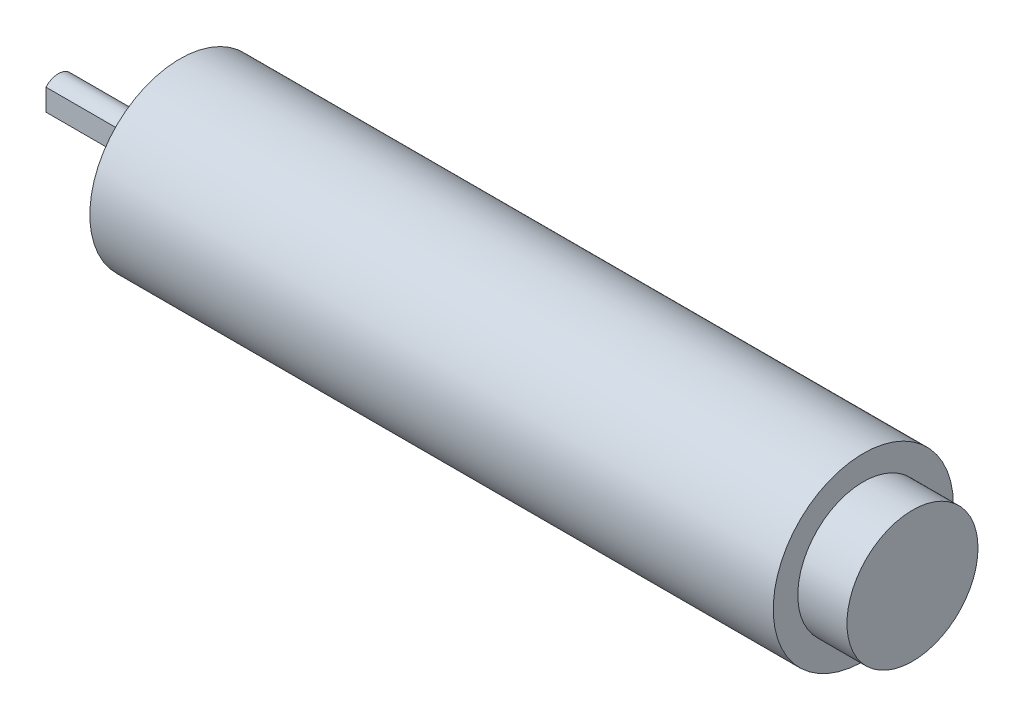
SolidWorks part; units mm, degrees
ref_plane "Front Plane" through (0, 0, 0) normal (0, 0, 1) x (1, 0, 0)
ref_plane "Top Plane" through (0, 0, 0) normal (0, 1, 0) x (1, 0, 0)
ref_plane "Right Plane" through (0, 0, 0) normal (1, 0, 0) x (0, 0, -1)
sketch "Sketch1" plane through (0, 0, 0) normal (0, 0, 1) x (1, 0, 0)
  line L0 (0, 11) -> (0, 0)
  line L1 (0, 0) -> (52.6, 0)
  line L2 (52.6, 0) -> (52.6, 11)
  line L3 (52.6, 11) -> (0, 11)
  line L4 (0, 0) -> (52.6, 0) construction
revolve "Revolve1" add sketch "Sketch1" angle 360 about L4
sketch "Sketch2" plane through (0, 0, 0) normal (-1, 0, 0) x (0, 0, 1)
  circle A0 centre (0, 0) radius 5
extrude "Boss-Extrude1" add sketch "Sketch2" along normal blind 1.35
sketch "Sketch3" plane through (-1.35, 0, 0) normal (-1, 0, 0) x (0, 0, 1)
  circle A0 centre (0, 0) radius 3.5
extrude "Boss-Extrude2" add sketch "Sketch3" along normal blind 1.8
sketch "Sketch4" plane through (-3.15, 0, 0) normal (-1, 0, 0) x (0, 0, 1)
  circle A0 centre (0, 0) radius 2
extrude "Boss-Extrude3" add sketch "Sketch4" along normal blind 11.7
ref_plane "Plane1" through (-3.675, 0, 3.675) normal (0.7071, 0, -0.7071) x (0, 1, 0)
sketch "Sketch6" plane through (-14.85, 0, 0) normal (-1, 0, 0) x (0, 0, 1)
  line L0 (1.5, 1.3229) -> (1.5, -1.3229)
  arc A0 (1.5, -1.3229) -> (1.5, 1.3229) centre (0, 0) ccw
extrude "Cut-Extrude1" cut sketch "Sketch6" against normal up to surface up to plane "Plane1"
hole_wizard "Hole1" positions "Sketch8" profile "Sketch7" legacy
sketch "Sketch8" plane through (0, 0, 0) normal (-1, 0, 0) x (0, 0, 1)
  point P0 (7, 0)
sketch "Sketch7" plane through (0, 0, 7) normal (0, 1, 0) x (0, 0, 1)
  line L0 (0, 0) -> (0, 6.5)
  line L1 (0, 6.5) -> (0.975, 6.5)
  line L2 (0.975, 6.5) -> (0.975, 0)
  line L3 (0.975, 0) -> (0, 0)
  line L4 (0, 110) -> (0, -10) construction
  dimension "Diameter" = 1.95
  dimension "Depth" = 6.5
hole_wizard "Hole2" positions "Sketch10" profile "Sketch9" legacy
sketch "Sketch10" plane through (0, 0, 0) normal (-1, 0, 0) x (0, 0, 1)
  point P0 (-3.5, -6.0622)
sketch "Sketch9" plane through (0, -6.0622, -3.5) normal (0, 1, 0) x (0, 0, 1)
  line L0 (0, 0) -> (0, 6.5)
  line L1 (0, 6.5) -> (0.975, 6.5)
  line L2 (0.975, 6.5) -> (0.975, 0)
  line L3 (0.975, 0) -> (0, 0)
  line L4 (0, 110) -> (0, -10) construction
  dimension "Diameter" = 1.95
  dimension "Depth" = 6.5
hole_wizard "Hole3" positions "Sketch12" profile "Sketch11" legacy
sketch "Sketch12" plane through (0, 0, 0) normal (-1, 0, 0) x (0, 0, 1)
  point P0 (-3.5, 6.0622)
sketch "Sketch11" plane through (0, 6.0622, -3.5) normal (0, 1, 0) x (0, 0, 1)
  line L0 (0, 0) -> (0, 6.5)
  line L1 (0, 6.5) -> (0.975, 6.5)
  line L2 (0.975, 6.5) -> (0.975, 0)
  line L3 (0.975, 0) -> (0, 0)
  line L4 (0, 110) -> (0, -10) construction
  dimension "Diameter" = 1.95
  dimension "Depth" = 6.5
hole_wizard "Hole4" positions "Sketch14" profile "Sketch13" legacy
sketch "Sketch14" plane through (52.6, 0, 0) normal (1, 0, 0) x (0, 0, -1)
  point P0 (0, 0)
sketch "Sketch13" plane through (52.6, 0, 0) normal (0, 1, 0) x (0, 0, -1)
  line L0 (0, 0) -> (0, 6.4)
  line L1 (0, 6.4) -> (3.5, 6.4)
  line L2 (3.5, 6.4) -> (3.5, 0)
  line L3 (3.5, 0) -> (0, 0)
  line L4 (0, 110) -> (0, -10) construction
  dimension "Diameter" = 7
  dimension "Depth" = 6.4
hole_wizard "Hole5" positions "Sketch16" profile "Sketch15" legacy
sketch "Sketch16" plane through (52.6, 0, 0) normal (1, 0, 0) x (0, 0, -1)
  point P0 (-8.5, 0)
sketch "Sketch15" plane through (52.6, 0, 8.5) normal (0, 1, 0) x (0, 0, -1)
  line L0 (0, 0) -> (0, 3)
  line L1 (0, 3) -> (1.05, 3)
  line L2 (1.05, 3) -> (1.05, 0)
  line L3 (1.05, 0) -> (0, 0)
  line L4 (0, 110) -> (0, -10) construction
  dimension "Diameter" = 2.1
  dimension "Depth" = 3
hole_wizard "Hole6" positions "Sketch18" profile "Sketch17" legacy
sketch "Sketch18" plane through (52.6, 0, 0) normal (1, 0, 0) x (0, 0, -1)
  point P0 (4.25, -7.3612)
sketch "Sketch17" plane through (52.6, -7.3612, -4.25) normal (0, 1, 0) x (0, 0, -1)
  line L0 (0, 0) -> (0, 3)
  line L1 (0, 3) -> (1.05, 3)
  line L2 (1.05, 3) -> (1.05, 0)
  line L3 (1.05, 0) -> (0, 0)
  line L4 (0, 110) -> (0, -10) construction
  dimension "Diameter" = 2.1
  dimension "Depth" = 3
hole_wizard "Hole7" positions "Sketch20" profile "Sketch19" legacy
sketch "Sketch20" plane through (52.6, 0, 0) normal (1, 0, 0) x (0, 0, -1)
  point P0 (4.25, 7.3612)
sketch "Sketch19" plane through (52.6, 7.3612, -4.25) normal (0, 1, 0) x (0, 0, -1)
  line L0 (0, 0) -> (0, 3)
  line L1 (0, 3) -> (1.05, 3)
  line L2 (1.05, 3) -> (1.05, 0)
  line L3 (1.05, 0) -> (0, 0)
  line L4 (0, 110) -> (0, -10) construction
  dimension "Diameter" = 2.1
  dimension "Depth" = 3
ref_plane "Plane2" through (52.6, 0, 0) normal (1, 0, 0) x (0, 0, -1)
sketch "Sketch25" plane through (52.6, 0, 0) normal (1, 0, 0) x (0, 0, -1)
  circle A0 centre (0, 0) radius 11
extrude "Boss-Extrude4" add sketch "Sketch25" along normal blind 36.83
sketch "Sketch26" plane through (89.43, 0, 0) normal (1, 0, 0) x (0, 0, -1)
  circle A0 centre (0, 0) radius 8
  circle A1 centre (0, 0) radius 12
  dimension "D1" = 16
  dimension "D2" = 24
extrude "Cut-Extrude2" cut sketch "Sketch26" against normal blind 6
